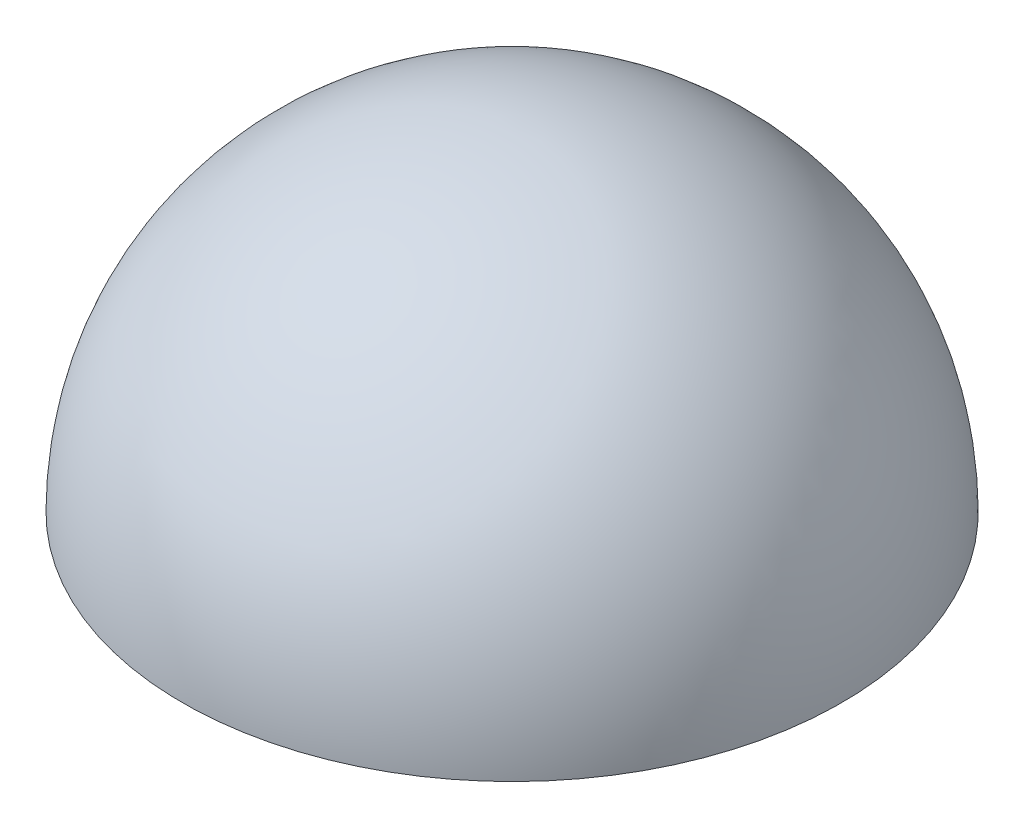
SolidWorks part; units mm, degrees
ref_plane "Front Plane" through (0, 0, 0) normal (0, 0, 1) x (1, 0, 0)
ref_plane "Top Plane" through (0, 0, 0) normal (0, 1, 0) x (1, 0, 0)
ref_plane "Right Plane" through (0, 0, 0) normal (1, 0, 0) x (0, 0, -1)
sketch "Sketch1" plane through (0, 0, 0) normal (0, 1, 0) x (1, 0, 0)
  line L0 (-55, 0) -> (55, 0) construction
  line L1 (-4, 0) -> (-6, 0)
  line L2 (4, 0) -> (6, 0)
  arc A0 (6, 0) -> (-6, 0) centre (0, 0) ccw
  arc A1 (4, 0) -> (-4, 0) centre (0, 0) ccw
  dimension "D1" = 4
  dimension "D2" = 6
revolve "Revolve2" add sketch "Sketch1" angle 180 about L0
